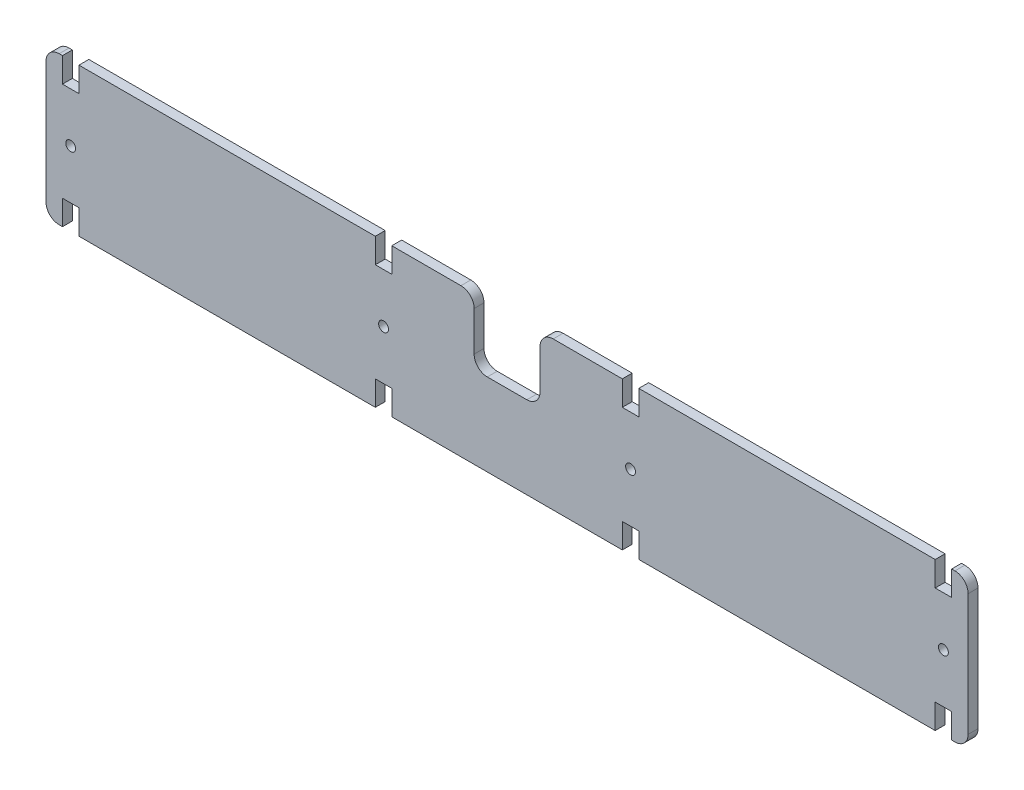
SolidWorks part; units mm, degrees
ref_plane "Plan de face" through (0, 0, 0) normal (0, 0, 1) x (1, 0, 0)
ref_plane "Plan de dessus" through (0, 0, 0) normal (0, 1, 0) x (1, 0, 0)
ref_plane "Plan de droite" through (0, 0, 0) normal (1, 0, 0) x (0, 0, -1)
sketch "Esquisse1" plane through (0, 0, 0) normal (0, 0, 1) x (1, 0, 0)
  line L0 (0, 0) -> (0, 45)
  line L1 (0, 45) -> (5, 45)
  line L2 (5, 45) -> (5, 37.5)
  line L3 (5, 37.5) -> (10, 37.5)
  line L4 (10, 37.5) -> (10, 45)
  line L5 (10, 45) -> (100, 45)
  line L6 (100, 45) -> (100, 37.5)
  line L7 (100, 37.5) -> (105, 37.5)
  line L8 (105, 37.5) -> (105, 45)
  line L9 (105, 45) -> (175, 45) construction
  line L10 (175, 45) -> (175, 37.5)
  line L11 (175, 37.5) -> (180, 37.5)
  line L12 (180, 37.5) -> (180, 45)
  line L13 (180, 45) -> (270, 45)
  line L14 (270, 45) -> (270, 37.5)
  line L15 (270, 37.5) -> (275, 37.5)
  line L16 (275, 37.5) -> (275, 45)
  line L17 (275, 45) -> (280, 45)
  line L18 (280, 45) -> (280, 0)
  line L19 (280, 0) -> (275, 0)
  line L20 (275, 0) -> (275, 7.5)
  line L21 (275, 7.5) -> (270, 7.5)
  line L22 (270, 7.5) -> (270, 0)
  line L23 (270, 0) -> (180, 0)
  line L24 (180, 0) -> (180, 7.5)
  line L25 (180, 7.5) -> (175, 7.5)
  line L26 (175, 7.5) -> (175, 0)
  line L27 (175, 0) -> (105, 0)
  line L28 (105, 0) -> (105, 7.5)
  line L29 (105, 7.5) -> (100, 7.5)
  line L30 (100, 7.5) -> (100, 0)
  line L31 (100, 0) -> (10, 0)
  line L32 (10, 0) -> (10, 7.5)
  line L33 (10, 7.5) -> (5, 7.5)
  line L34 (5, 7.5) -> (5, 0)
  line L35 (5, 0) -> (0, 0)
  line L36 (0, 22.5) -> (280, 22.5) construction
  line L37 (7.5, 37.5) -> (7.5, 7.5) construction
  line L38 (102.5, 7.5) -> (102.5, 37.5) construction
  line L39 (177.5, 37.5) -> (177.5, 7.5) construction
  line L40 (272.5, 7.5) -> (272.5, 37.5) construction
  line L41 (105, 45) -> (130, 45)
  line L42 (130, 45) -> (130, 25)
  line L43 (130, 25) -> (150, 25)
  line L44 (150, 25) -> (150, 45)
  line L45 (150, 45) -> (175, 45)
  line L46 (140, 45) -> (140, 0) construction
  circle A0 centre (7.5, 22.5) radius 1.5
  circle A1 centre (102.5, 22.5) radius 1.5
  circle A2 centre (177.5, 22.5) radius 1.5
  circle A3 centre (272.5, 22.5) radius 1.5
  point P61 (0, 0)
  dimension "D7" = 3
  dimension "D1" = 5
  dimension "D2" = 5
  dimension "D3" = 90
  dimension "D4" = 70
  dimension "D5" = 45
  dimension "D6" = 30
  dimension "D8" = 20
  dimension "D9" = 20
extrude "Boss.-Extru.1" add sketch "Esquisse1" along normal blind 3
fillet "Congé1" radius 4 8 edges at (150, 45, 1.5) (130, 45, 1.5) (130, 25, 1.5) (150, 25, 1.5) (280, 45, 1.5) (280, 0, 1.5) (0, 0, 1.5) (0, 45, 1.5)
